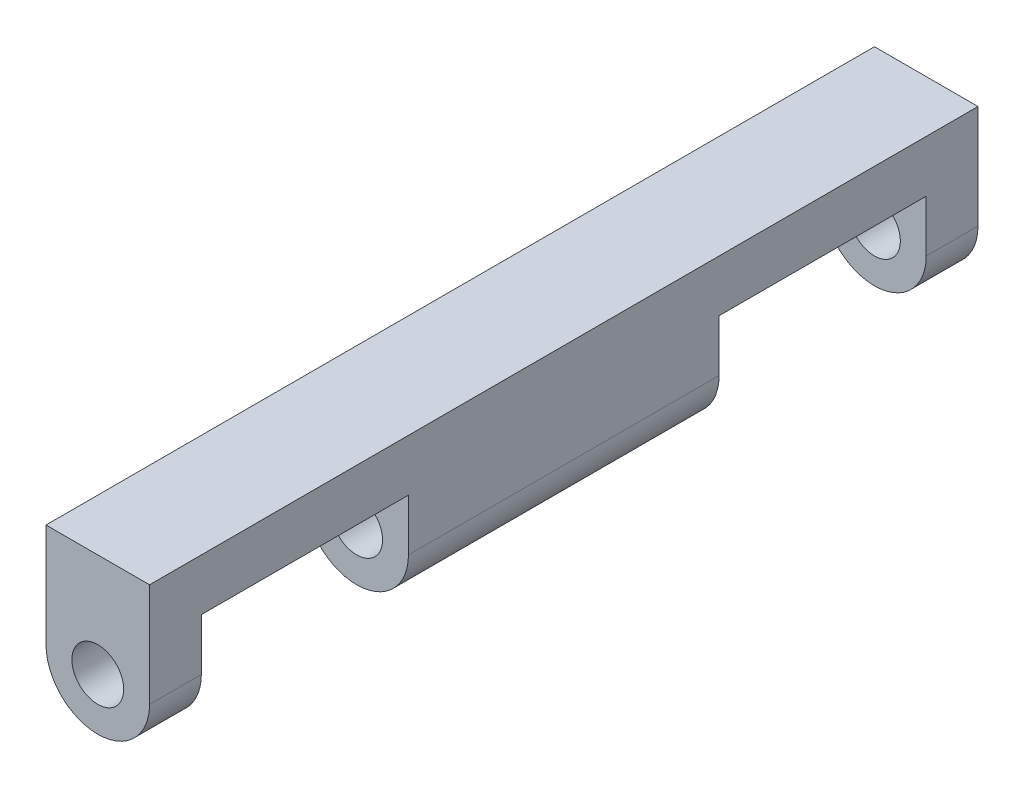
SolidWorks part; units mm, degrees
ref_plane "前视基准面" through (0, 0, 0) normal (0, 0, 1) x (1, 0, 0)
ref_plane "上视基准面" through (0, 0, 0) normal (0, 1, 0) x (1, 0, 0)
ref_plane "右视基准面" through (0, 0, 0) normal (1, 0, 0) x (0, 0, -1)
other "Configuration Table"
sketch "草图1" plane through (0, 0, 0) normal (0, 0, 1) x (1, 0, 0)
  line L0 (0, 0) -> (0, 10.3531) construction
  line L1 (-5, 10) -> (5, 10)
  line L2 (5, 10) -> (5, 0)
  line L3 (-5, 10) -> (-5, 0)
  arc A0 (-5, 0) -> (5, 0) centre (0, 0) ccw
  circle A1 centre (0, 0) radius 2.5
  point P10 (0, 10)
  dimension "D1" = 10
  dimension "D3" = 5
  dimension "D2" = 10
extrude "凸台-拉伸1" add sketch "草图1" along normal blind 80
sketch "草图2" plane through (5, 0, 0) normal (1, 0, 0) x (0, 0, -1)
  line L0 (-40, 22.3675) -> (-40, -12.8702) construction
  line L1 (0, 0) -> (0, 10) construction
  line L2 (-80, 0) -> (-80, 10) construction
  line L3 (-80, 10) -> (0, 10) construction
  line L4 (-25, 5) -> (-5, 5)
  line L5 (-25, 5) -> (-25, -10)
  line L6 (-25, -10) -> (-5, -10)
  line L7 (-5, 5) -> (-5, -10)
  line L8 (-75, 5) -> (-55, 5)
  line L9 (-75, 5) -> (-75, -10)
  line L10 (-75, -10) -> (-55, -10)
  line L11 (-55, 5) -> (-55, -10)
  dimension "D1" = 5
  dimension "D2" = 5
  dimension "D3" = 20
  dimension "D4" = 20
  dimension "D5" = 5
  dimension "D6" = 5
  dimension "D7" = 15
  dimension "D8" = 15
extrude "切除-拉伸1" cut sketch "草图2" against normal blind 80
